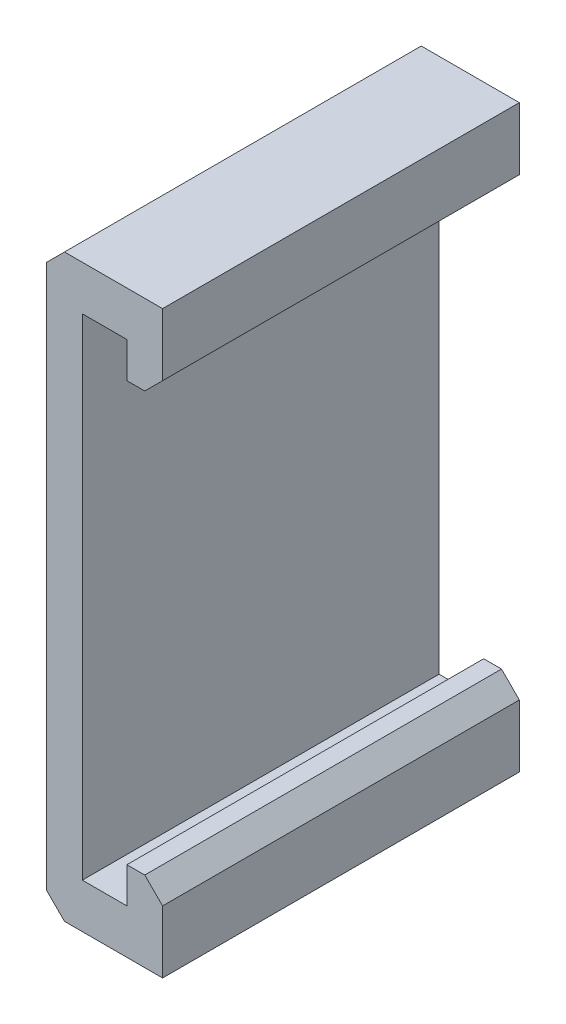
SolidWorks part; units mm, degrees
ref_plane "Front Plane" through (0, 0, 0) normal (0, 0, 1) x (1, 0, 0)
ref_plane "Top Plane" through (0, 0, 0) normal (0, 1, 0) x (1, 0, 0)
ref_plane "Right Plane" through (0, 0, 0) normal (1, 0, 0) x (0, 0, -1)
sketch "Sketch1" plane through (0, 0, 0) normal (0, 0, 1) x (1, 0, 0)
  line L0 (2.2, 21.2) -> (2.6, 21.6)
  line L1 (2.6, 21.6) -> (2.6, 23)
  line L2 (2.6, 23) -> (0.4, 23)
  line L3 (0.4, 23) -> (0, 22.6)
  line L4 (0, 22.6) -> (0, 10.4)
  line L5 (0, 10.4) -> (0.4, 10)
  line L6 (0.4, 10) -> (2.6, 10)
  line L7 (2.6, 10) -> (2.6, 11.4)
  line L8 (2.6, 11.4) -> (2.2, 11.8)
  line L9 (2.2, 11.8) -> (1.8, 11.8)
  line L10 (1.8, 11.8) -> (1.8, 11)
  line L11 (1.8, 11) -> (0.8, 11)
  line L12 (0.8, 11) -> (0.8, 22)
  line L13 (0.8, 22) -> (1.8, 22)
  line L14 (1.8, 22) -> (1.8, 21.2)
  line L15 (1.8, 21.2) -> (2.2, 21.2)
extrude "Boss-Extrude1" add sketch "Sketch1" against normal blind 8
